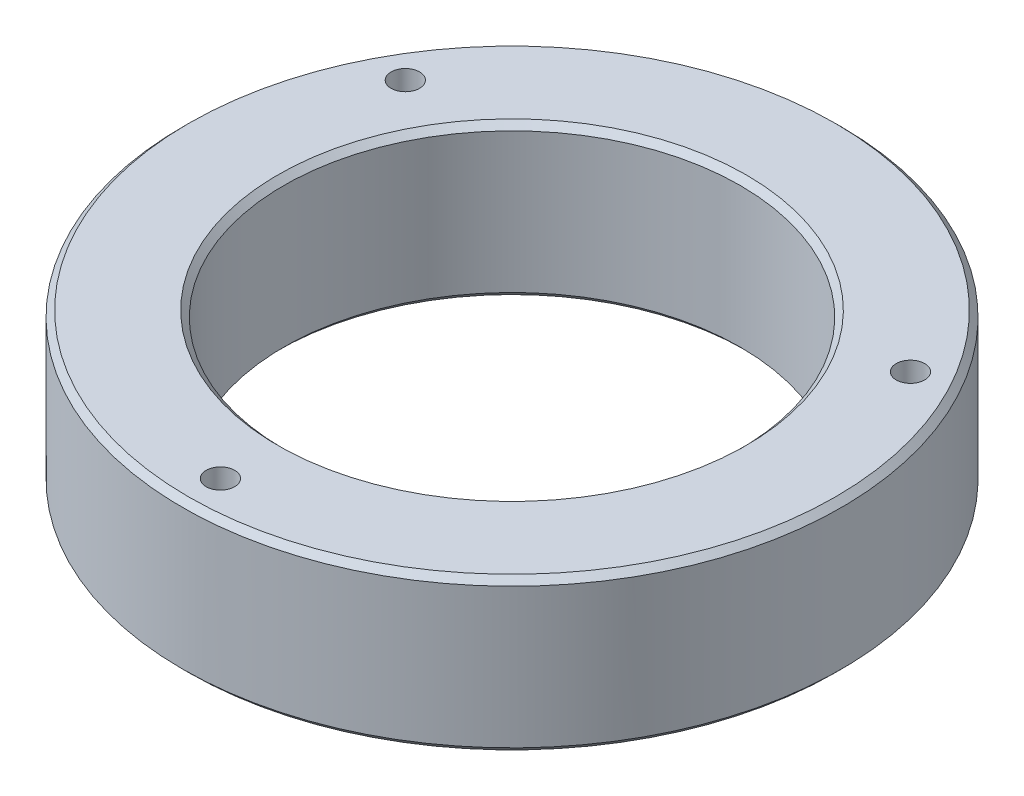
SolidWorks part; units mm, degrees
ref_plane "Front Plane" through (0, 0, 0) normal (1, 0, 0) x (0, 1, 0)
ref_plane "Top Plane" through (0, 0, 0) normal (0, 0, 1) x (0, 1, 0)
ref_plane "Right Plane" through (0, 0, 0) normal (0, 1, 0) x (-1, 0, 0)
sketch "Sketch1" plane through (0, 0, 0) normal (0, 0, 1) x (0, 1, 0)
  line L0 (-19.05, 82.5246) -> (19.05, 82.5246)
  line L1 (19.05, 82.5246) -> (19.05, 57.15)
  line L2 (19.05, 57.15) -> (-19.05, 57.15)
  line L3 (-19.05, 57.15) -> (-19.05, 82.5246)
  line L4 (-44.45, 0) -> (44.45, 0) construction
revolve "Revolve1" add sketch "Sketch1" angle 360 about L4
chamfer "Chamfer1" distance 1.524 angle 45 4 edges at (0, 19.05, -57.15) (0, -19.05, -57.15) (0, 19.05, -82.5246) (0, -19.05, -82.5246)
hole_wizard "CBORE for 1/4 Socket Head Cap Screw1" positions "Sketch3" profile "Sketch2" counterbore size "1/4" standard "ANSI Inch"
sketch "Sketch3" plane through (0, -19.05, 0) normal (0, -1, 0) x (-1, 0, 0)
  point P0 (0, -73.025)
  point P1 (-63.246, 36.5252)
  point P3 (63.246, 36.5252)
sketch "Sketch2" plane through (0, -19.05, 73.025) normal (1, 0, 0) x (0, 0, -1)
  line L0 (0, 0) -> (0, 40.2443)
  line L1 (0, 40.2443) -> (3.5687, 38.1)
  line L2 (3.5687, 38.1) -> (3.5687, 9.652)
  line L3 (3.5687, 9.652) -> (5.5626, 9.652)
  line L4 (5.5626, 9.652) -> (5.5626, 0)
  line L5 (5.5626, 0) -> (0, 0)
  line L10 (0, 40.2443) -> (-3.5687, 38.1) construction
  line L11 (0, -6.35) -> (0, 107.95) construction
  dimension "Hole Dia." = 7.1374
  dimension "Hole Depth" = 38.1
  dimension "C'Bore Dia." = 11.1252
  dimension "C'Bore Depth" = 9.652
  dimension "Drill Angle" = 118
sketch "Sketch4" plane through (0, 0, 0) normal (0, 1, 0) x (-1, 0, 0)
  circle A0 centre (-69.85, 0) radius 3.9687
  circle A1 centre (69.85, 0) radius 3.9687
extrude "Cut-Extrude2" cut sketch "Sketch4" along normal blind 25.4 from offset 19.05
